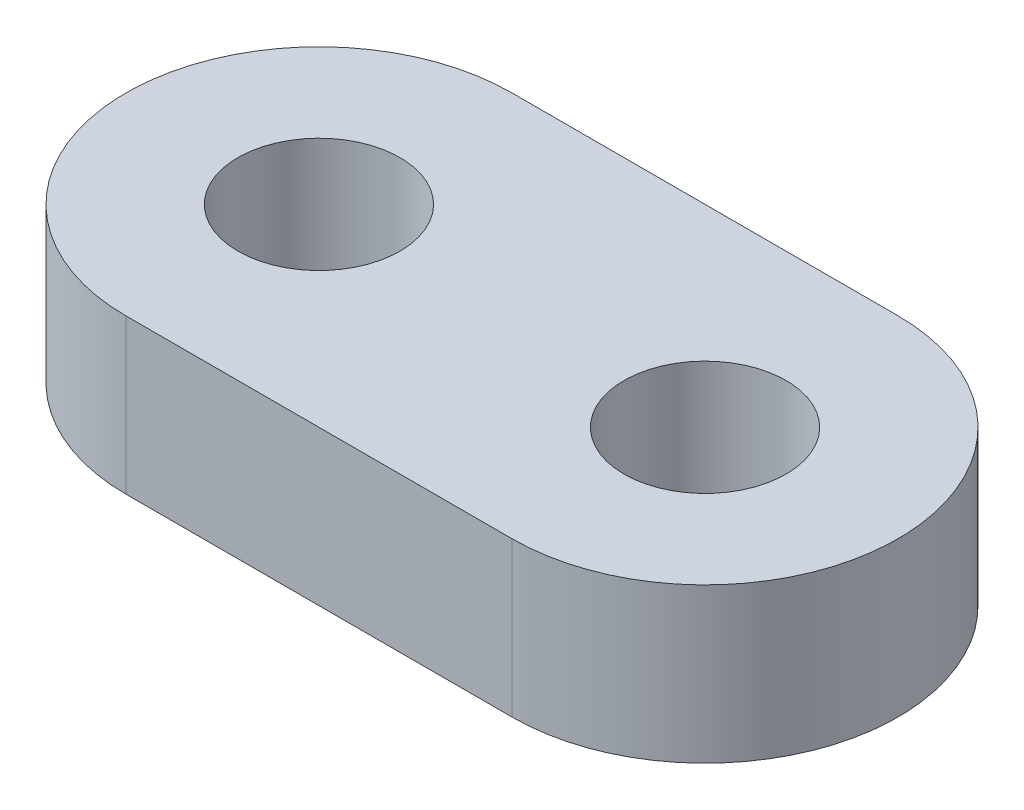
SolidWorks part; units mm, degrees
ref_plane "Front Plane" through (0, 0, 0) normal (0, 0, 1) x (1, 0, 0)
ref_plane "Top Plane" through (0, 0, 0) normal (0, 1, 0) x (1, 0, 0)
ref_plane "Right Plane" through (0, 0, 0) normal (1, 0, 0) x (0, 0, -1)
sketch "Sketch1" plane through (0, 0, 0) normal (0, 1, 0) x (1, 0, 0)
  line L0 (0, 0) -> (5, 0) construction
  line L1 (0, 2.5) -> (5, 2.5)
  line L2 (0, -2.5) -> (5, -2.5)
  arc A0 (0, 2.5) -> (0, -2.5) centre (0, 0) ccw
  arc A1 (5, -2.5) -> (5, 2.5) centre (5, 0) ccw
  circle A2 centre (0, 0) radius 1.05
  circle A3 centre (5, 0) radius 1.05
  point P3 (2.5, 0)
  dimension "D2" = 2.5
  dimension "D4" = 2.1
  dimension "D5" = 2.1
  dimension "D1" = 5
extrude "Boss-Extrude1" add sketch "Sketch1" along normal blind 2
